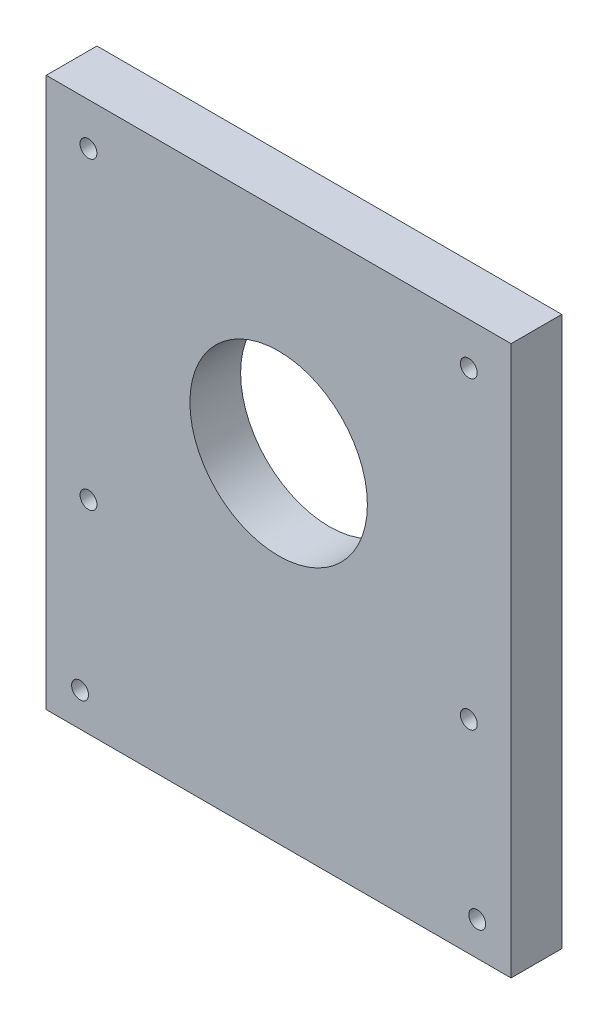
SolidWorks part; units mm, degrees
ref_plane "Front Plane" through (0, 0, 0) normal (0, 0, 1) x (1, 0, 0)
ref_plane "Top Plane" through (0, 0, 0) normal (0, 1, 0) x (1, 0, 0)
ref_plane "Right Plane" through (0, 0, 0) normal (1, 0, 0) x (0, 0, -1)
sketch "Sketch1" plane through (0, 0, 0) normal (0, 0, 1) x (1, 0, 0)
  line L1 (-55, -65) -> (55, -65)
  line L2 (-55, -65) -> (-55, 65)
  line L3 (-55, 65) -> (55, 65)
  line L4 (55, -65) -> (55, 65)
  line L5 (-55, -65) -> (55, 65) construction
  line L6 (-55, 65) -> (55, -65) construction
  point P0 (0, 0)
  dimension "D1" = 110
  dimension "D2" = 130
extrude "Boss-Extrude1" add sketch "Sketch1" along normal blind 12
sketch "Sketch2" plane through (0, 0, 0) normal (0, 0, -1) x (-1, 0, 0)
  line L0 (0, 65) -> (0, -65) construction
  line L1 (-55, 65) -> (55, 65) construction
  line L2 (55, -65) -> (-55, -65) construction
  line L3 (-55, -65) -> (-55, 65) construction
  circle A0 centre (-45, 55) radius 2
  circle A1 centre (-45, -17) radius 2
  circle A2 centre (-47, -57) radius 2
  circle A3 centre (47, -57) radius 2
  circle A4 centre (45, -17) radius 2
  circle A5 centre (45, 55) radius 2
  dimension "D1" = 4
  dimension "D2" = 4
  dimension "D3" = 4
  dimension "D4" = 10
  dimension "D5" = 10
  dimension "D6" = 8
  dimension "D7" = 8
  dimension "D8" = 48
  dimension "D9" = 10
extrude "Cut-Extrude1" cut sketch "Sketch2" against normal through all and the other way through all
sketch "Sketch3" plane through (0, 0, 12) normal (0, 0, 1) x (1, 0, 0)
  line L0 (55, 65) -> (-55, 65) construction
  circle A0 centre (0, 15) radius 21
  dimension "D1" = 50
  dimension "D2" = 42
extrude "Cut-Extrude2" cut sketch "Sketch3" against normal through all
